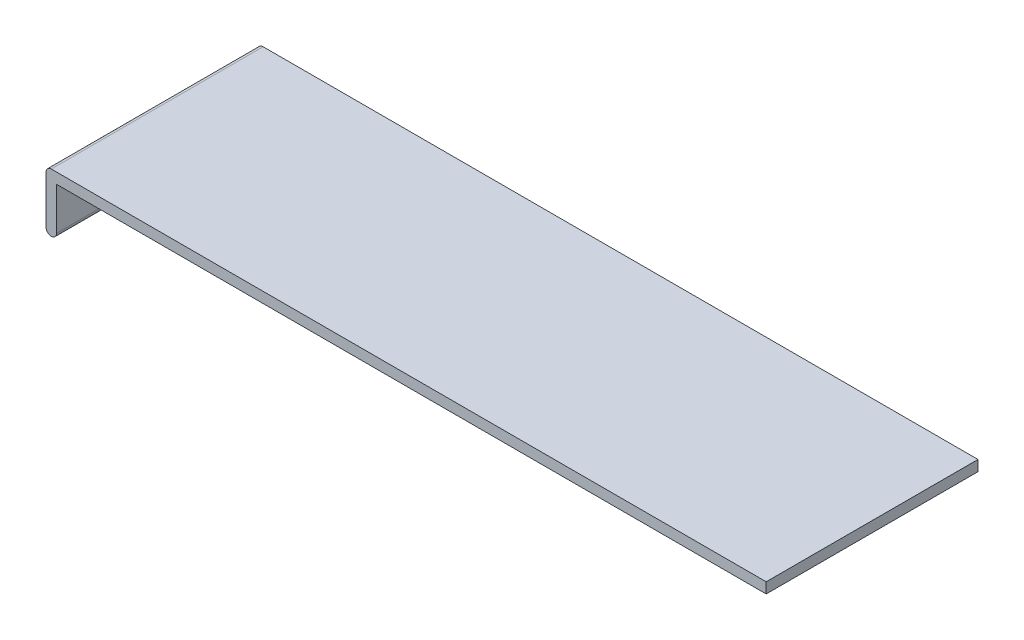
SolidWorks part; units mm, degrees
ref_plane "Plano frontal" through (0, 0, 0) normal (0, 0, 1) x (1, 0, 0)
ref_plane "Plano superior" through (0, 0, 0) normal (0, 1, 0) x (1, 0, 0)
ref_plane "Plano direito" through (0, 0, 0) normal (1, 0, 0) x (0, 0, -1)
sketch "Esboço1" plane through (0, 0, 0) normal (0, 0, 1) x (1, 0, 0)
  line L0 (0.1, 0) -> (0.1, 0.8)
  line L1 (0.1, 0.8) -> (13.5, 0.8)
  line L2 (-0.1, 0) -> (-0.1, 0.8)
  line L3 (-0.1, 0.8) -> (-0.1, 0.9)
  line L4 (0, 1) -> (13.5, 1)
  line L8 (13.5, 1) -> (13.5, 0.8)
  arc A0 (-0.1, 0) -> (0.1, 0) centre (0, 0) ccw
  arc A1 (0, 1) -> (-0.1, 0.9) centre (0, 0.9) ccw
extrude "Ressalto-extrusão1" add sketch "Esboço1" along normal blind 4
